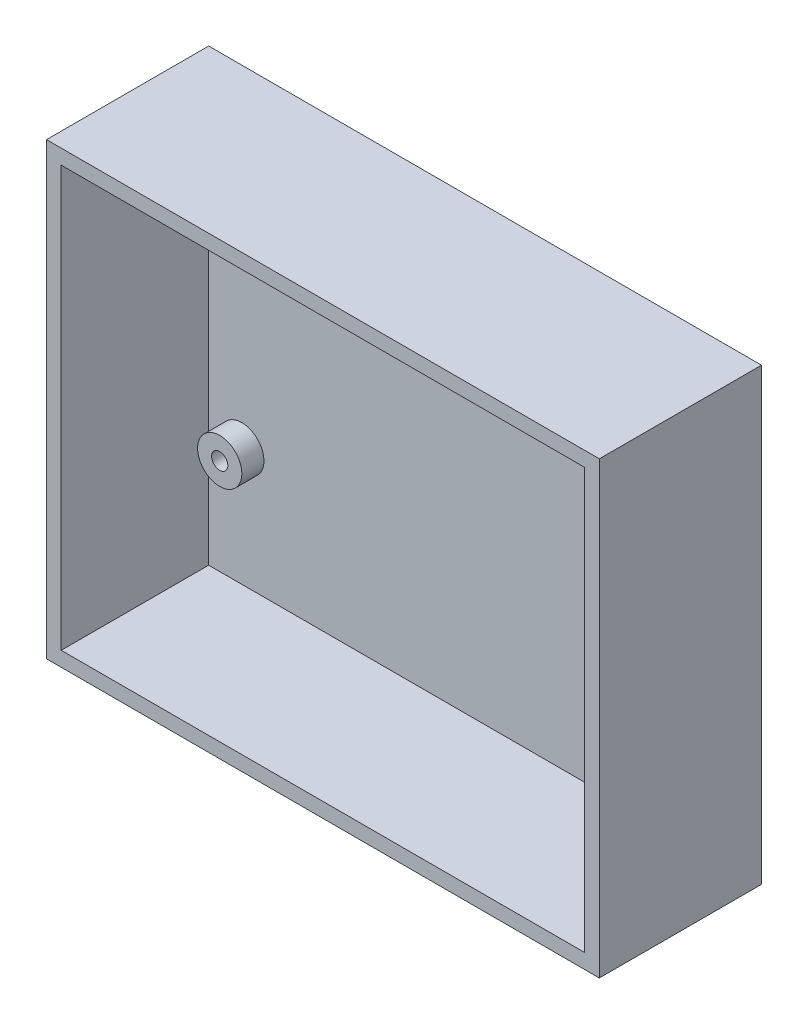
SolidWorks part; units mm, degrees
ref_plane "前视基准面" through (0, 0, 0) normal (0, 0, 1) x (1, 0, 0)
ref_plane "上视基准面" through (0, 0, 0) normal (0, 1, 0) x (1, 0, 0)
ref_plane "右视基准面" through (0, 0, 0) normal (1, 0, 0) x (0, 0, -1)
other "Configuration Table"
sketch "草图1" plane through (0, 0, 0) normal (0, 0, 1) x (1, 0, 0)
  line L1 (0, 0) -> (75, 0)
  line L2 (0, 0) -> (0, 61)
  line L3 (0, 61) -> (75, 61)
  line L4 (75, 0) -> (75, 61)
extrude "凸台-拉伸1" add sketch "草图1" along normal blind 22
sketch "草图2" plane through (0, 0, 0) normal (0, 0, 1) x (1, 0, 0)
  line L1 (2, 2) -> (73, 2)
  line L2 (2, 2) -> (2, 59)
  line L3 (2, 59) -> (73, 59)
  line L4 (73, 2) -> (73, 59)
extrude "切除-拉伸1" cut sketch "草图2" along normal through all
sketch "草图3" plane through (0, 0, 0) normal (0, 0, 1) x (1, 0, 0)
  line L1 (0, 0) -> (75, 0)
  line L2 (0, 0) -> (0, 61)
  line L3 (0, 61) -> (75, 61)
  line L4 (75, 0) -> (75, 61)
extrude "凸台-拉伸2" add sketch "草图3" along normal blind 2
sketch "草图4" plane through (0, 0, 0) normal (0, 0, 1) x (1, 0, 0)
  circle A0 centre (6.5, 18) radius 3
  circle A1 centre (68.5, 18) radius 3
  circle A2 centre (6.5, 54) radius 3
  circle A3 centre (68.5, 54) radius 3
extrude "凸台-拉伸3" add sketch "草图4" along normal blind 5
sketch "草图5" plane through (0, 0, 0) normal (0, 0, 1) x (1, 0, 0)
  circle A0 centre (6.5, 18) radius 1.1
  circle A1 centre (68.5, 18) radius 1.1
  circle A2 centre (6.5, 54) radius 1.1
  circle A3 centre (68.5, 54) radius 1.1
extrude "切除-拉伸2" cut sketch "草图5" along normal through all
